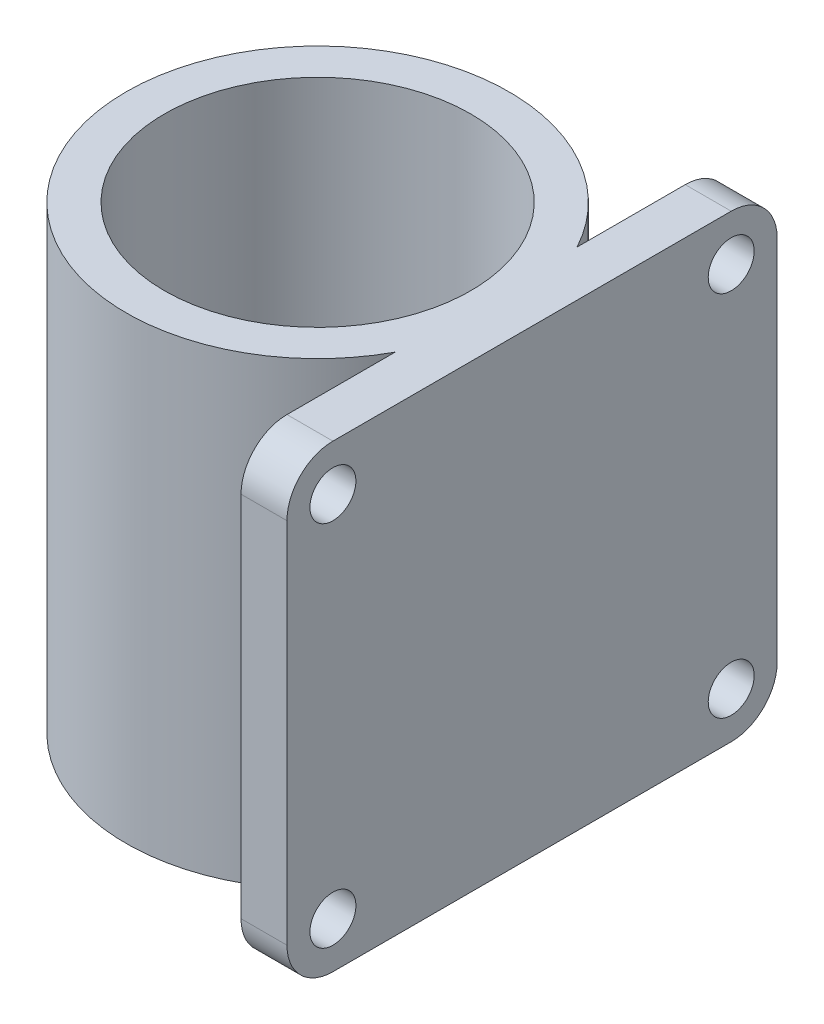
SolidWorks part; units mm, degrees
ref_plane "前视基准面" through (0, 0, 0) normal (0, 0, 1) x (1, 0, 0)
ref_plane "上视基准面" through (0, 0, 0) normal (0, 1, 0) x (1, 0, 0)
ref_plane "右视基准面" through (0, 0, 0) normal (1, 0, 0) x (0, 0, -1)
sketch "草图1" plane through (0, 0, 0) normal (0, 1, 0) x (1, 0, 0)
  circle A0 centre (0, 0) radius 10
  circle A1 centre (0, 0) radius 12.5
extrude "凸台-拉伸1" add sketch "草图1" along normal blind 30
sketch "草图2" plane through (0, 0, 0) normal (0, 1, 0) x (1, 0, 0)
  line L0 (15, 0) -> (10, 0) construction
  line L2 (11, -16) -> (14, -16)
  line L3 (11, -16) -> (11, 16)
  line L4 (11, 16) -> (14, 16)
  line L5 (14, -16) -> (14, 16)
  line L6 (11, -16) -> (14, 16) construction
  line L7 (11, 16) -> (14, -16) construction
  circle A0 centre (0, 0) radius 10 construction
  point P5 (12.5, 0)
extrude "凸台-拉伸2" add sketch "草图2" along normal blind 30
sketch "草图4" plane through (11, 0, 0) normal (-1, 0, 0) x (0, 0, 1)
  line L0 (16, 30) -> (-16, 0) construction
  line L1 (0, 15) -> (13.1657, 0.9565)
  line L2 (15.2167, 27) -> (14.0083, 29.0929)
  line L3 (14.0083, 29.0929) -> (11.5917, 29.0929)
  line L4 (11.5917, 29.0929) -> (10.3833, 27)
  line L5 (10.3833, 27) -> (11.5917, 24.9071)
  line L6 (11.5917, 24.9071) -> (14.0083, 24.9071)
  line L7 (14.0083, 24.9071) -> (15.2167, 27)
  line L8 (-10.7893, 1.6593) -> (-12.9558, 0.5884)
  line L9 (-10.6336, 4.0709) -> (-10.7893, 1.6593)
  line L10 (-12.6442, 5.4116) -> (-10.6336, 4.0709)
  line L11 (-14.8107, 4.3407) -> (-12.6442, 5.4116)
  line L12 (-14.9664, 1.9291) -> (-14.8107, 4.3407)
  line L13 (-12.9558, 0.5884) -> (-14.9664, 1.9291)
  line L14 (0, 15) -> (0, 30) construction
  line L15 (12.5, 30) -> (-12.5, 30) construction
  line L16 (12.9558, 0.5884) -> (14.9664, 1.9291)
  line L17 (14.9664, 1.9291) -> (14.8107, 4.3407)
  line L18 (14.8107, 4.3407) -> (12.6442, 5.4116)
  line L19 (12.6442, 5.4116) -> (10.6336, 4.0709)
  line L20 (10.6336, 4.0709) -> (10.7893, 1.6593)
  line L21 (10.7893, 1.6593) -> (12.9558, 0.5884)
  line L22 (-14.0083, 24.9071) -> (-15.2167, 27)
  line L23 (-11.5917, 24.9071) -> (-14.0083, 24.9071)
  line L24 (-10.3833, 27) -> (-11.5917, 24.9071)
  line L25 (-11.5917, 29.0929) -> (-10.3833, 27)
  line L26 (-14.0083, 29.0929) -> (-11.5917, 29.0929)
  line L27 (-15.2167, 27) -> (-14.0083, 29.0929)
  circle A0 centre (12.8, 27) radius 2.0929 construction
  circle A1 centre (-12.8, 3) radius 2.0929 construction
  circle A2 centre (12.8, 3) radius 2.0929 construction
  circle A3 centre (-12.8, 27) radius 2.0929 construction
  dimension "D1" = 3
extrude "切除-拉伸2" cut sketch "草图4" against normal blind 0.5 contours L11 L10 L9 L8 L13 L12 | L6 L7 L2 L3 L4 L5 | L26 L25 L24 L23 L22 L27 | L19 L20 L21 L16 L17 L18
sketch "草图5" plane through (11.5, 0, 0) normal (-1, 0, 0) x (0, 0, 1)
  line L0 (-16, 30) -> (-16, 0) construction
  circle A0 centre (-13, 27) radius 1.5
  circle A1 centre (13, 27) radius 1.5
  circle A2 centre (13, 3) radius 1.5
  circle A3 centre (-13, 3) radius 1.5
  dimension "D1" = 26
  dimension "D2" = 3
  dimension "D3" = 26
  dimension "D4" = 3
  dimension "D5" = 24
extrude "切除-拉伸3" cut sketch "草图5" against normal through all
fillet "圆角1" radius 3 4 edges at (12.5, 0, 16) (12.5, 30, 16) (12.5, 0, -16) (12.5, 30, -16)
